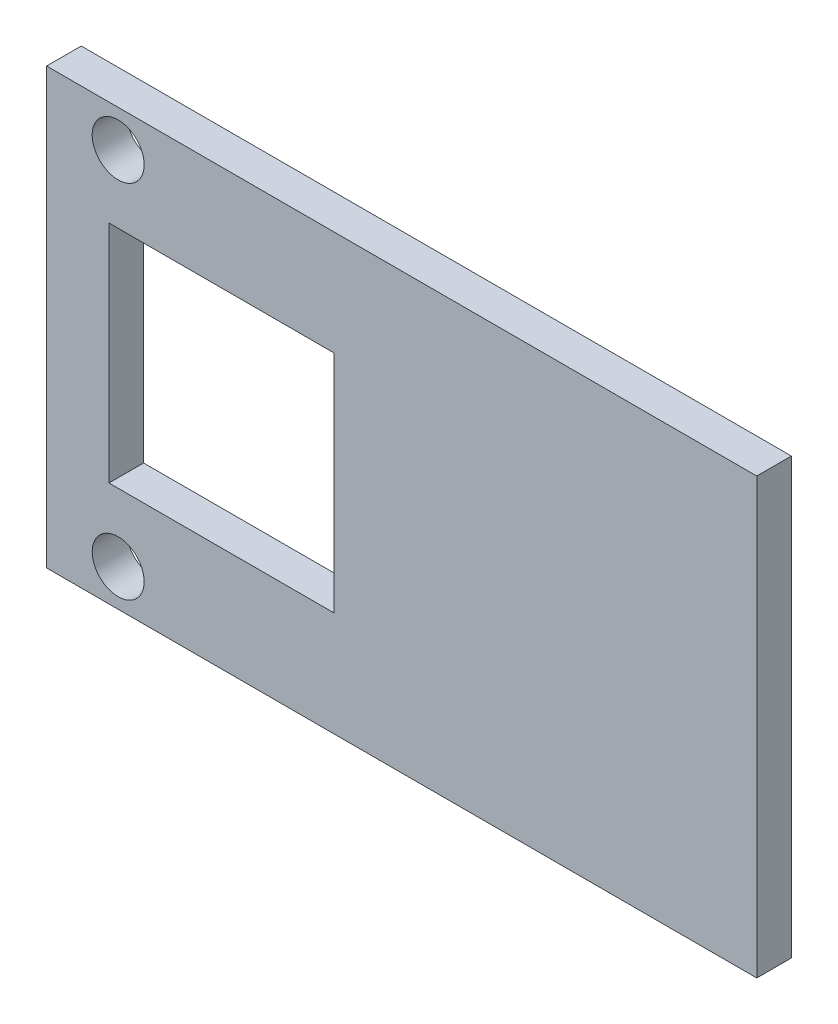
SolidWorks part; units mm, degrees
ref_plane "Plano frontal" through (0, 0, 0) normal (0, 0, 1) x (1, 0, 0)
ref_plane "Plano superior" through (0, 0, 0) normal (0, 1, 0) x (1, 0, 0)
ref_plane "Plano direito" through (0, 0, 0) normal (1, 0, 0) x (0, 0, -1)
sketch "Esboço1" plane through (0, 0, 0) normal (0, 0, 1) x (1, 0, 0)
  line L1 (0, 0) -> (35, 0)
  line L2 (0, 0) -> (0, 25.1)
  line L3 (0, 25.1) -> (35, 25.1)
  line L4 (35, 0) -> (35, 25.1)
extrude "Ressalto-extrusão1" add sketch "Esboço1" along normal blind 2
sketch "Esboço2" plane through (0, 0, 2) normal (0, 0, 1) x (1, 0, 0)
  line L0 (0, 12.55) -> (6.2733, 12.55) construction
  line L2 (0, 25.1) -> (0, 0) construction
  circle A0 centre (2.13, 22.97) radius 1.5
  circle A1 centre (2.13, 2.13) radius 1.5
extrude "Corte-extrusão1" cut sketch "Esboço2" against normal blind 2
sketch "Esboço3" plane through (0, 0, 2) normal (0, 0, 1) x (1, 0, 0)
  line L0 (0, 25.1) -> (-2.0029, 25.1)
  line L1 (-2.0029, 25.1) -> (-2.0029, 0)
  line L2 (-2.0029, 0) -> (0, 0)
  line L3 (0, 0) -> (0, 25.1)
extrude "Ressalto-extrusão2" add sketch "Esboço3" against normal blind 2
sketch "Esboço4" plane through (0, 0, 2) normal (0, 0, 1) x (1, 0, 0)
  line L2 (1.5971, 12.55) -> (1.5971, 19.05)
  line L3 (1.5971, 19.05) -> (14.5971, 19.05)
  line L4 (14.5971, 19.05) -> (14.5971, 6.05)
  line L5 (14.5971, 6.05) -> (1.5971, 6.05)
  line L6 (1.5971, 6.05) -> (1.5971, 12.55)
extrude "Corte-extrusão2" cut sketch "Esboço4" against normal blind 2
sketch "Esboço5" plane through (0, 0, 2) normal (0, 0, 1) x (1, 0, 0)
  line L0 (35, 25.1) -> (39, 25.1)
  line L1 (39, 25.1) -> (39, 0)
  line L2 (39, 0) -> (35, 0)
  line L3 (35, 0) -> (35, 25.1) construction
  line L4 (35, 0) -> (35, 25.1)
extrude "Ressalto-extrusão3" add sketch "Esboço5" against normal blind 2
